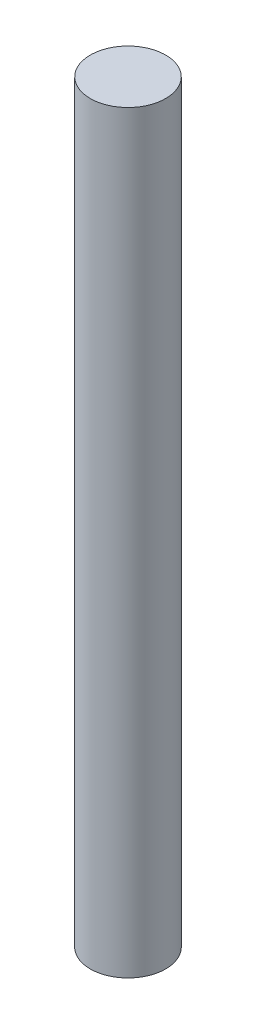
SolidWorks part; units mm, degrees
ref_plane "Front Plane" through (0, 0, 0) normal (0, 0, 1) x (1, 0, 0)
ref_plane "Top Plane" through (0, 0, 0) normal (0, 1, 0) x (1, 0, 0)
ref_plane "Right Plane" through (0, 0, 0) normal (1, 0, 0) x (0, 0, -1)
sketch "Sketch2" plane through (0, 0, 0) normal (0, 1, 0) x (1, 0, 0)
  circle A0 centre (0, 0) radius 10
extrude "Boss-Extrude2" add sketch "Sketch2" along normal blind 200
